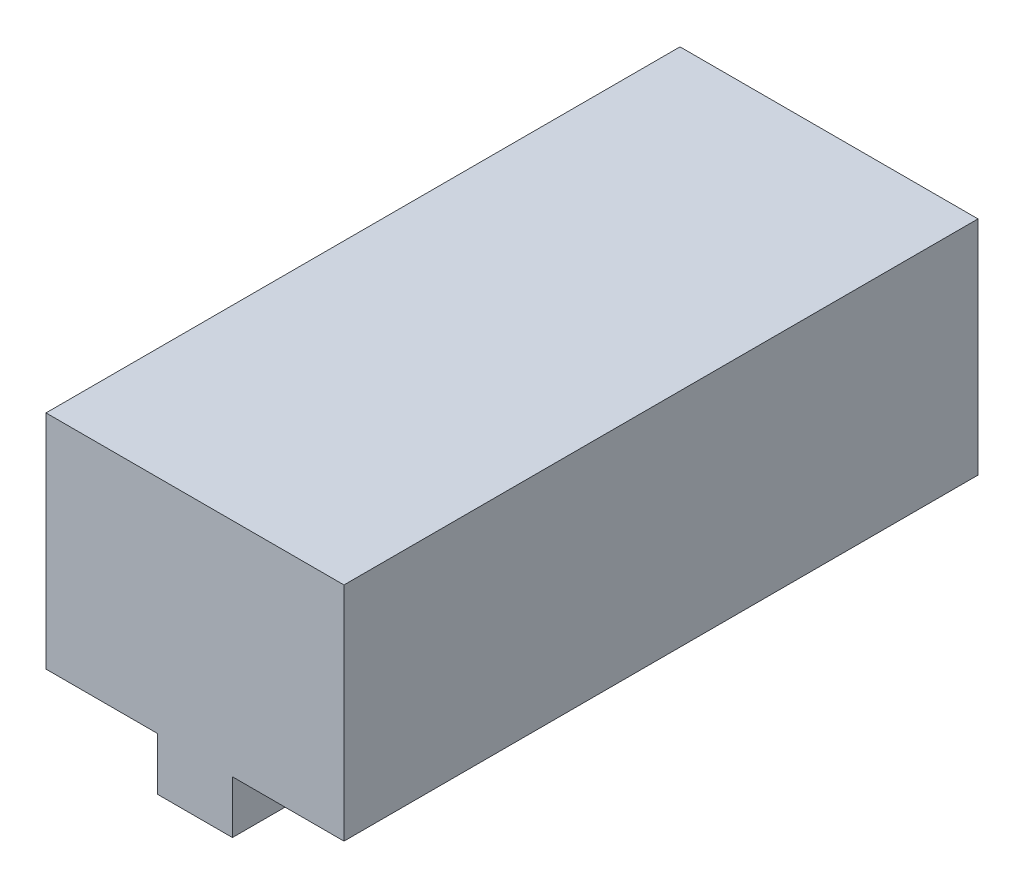
SolidWorks part; units mm, degrees
ref_plane "Front" through (0, 0, 0) normal (0, 0, 1) x (1, 0, 0)
ref_plane "Top" through (0, 0, 0) normal (0, 1, 0) x (1, 0, 0)
ref_plane "Right" through (0, 0, 0) normal (1, 0, 0) x (0, 0, -1)
sketch "Sketch1" plane through (0, 0, 0) normal (0, 0, 1) x (1, 0, 0)
  line L1 (0, 0) -> (11.938, 0)
  line L2 (0, 0) -> (0, 8.89)
  line L4 (11.938, 0) -> (11.938, 8.89)
  line L9 (0, 8.89) -> (11.938, 8.89)
  dimension "D1" = 11.938
  dimension "D2" = 8.89
extrude "Boss-Extrude1" add sketch "Sketch1" against normal blind 25.4 contours L9 L4 L1 L2
sketch "Sketch2" plane through (0, 0, 0) normal (0, 0, 1) x (1, 0, 0)
  line L0 (0, 8.89) -> (11.938, 8.89) construction
  line L1 (4.469, -2.11) -> (7.469, -2.11)
  line L2 (4.469, -2.11) -> (4.469, 0)
  line L3 (4.469, 0) -> (7.469, 0)
  line L4 (7.469, -2.11) -> (7.469, 0)
  line L5 (5.969, 8.89) -> (5.969, -2.11) construction
  dimension "D1" = 11
  dimension "D2" = 3
extrude "Boss-Extrude2" add sketch "Sketch2" against normal blind 15 contours L1 L4 L3 L2
